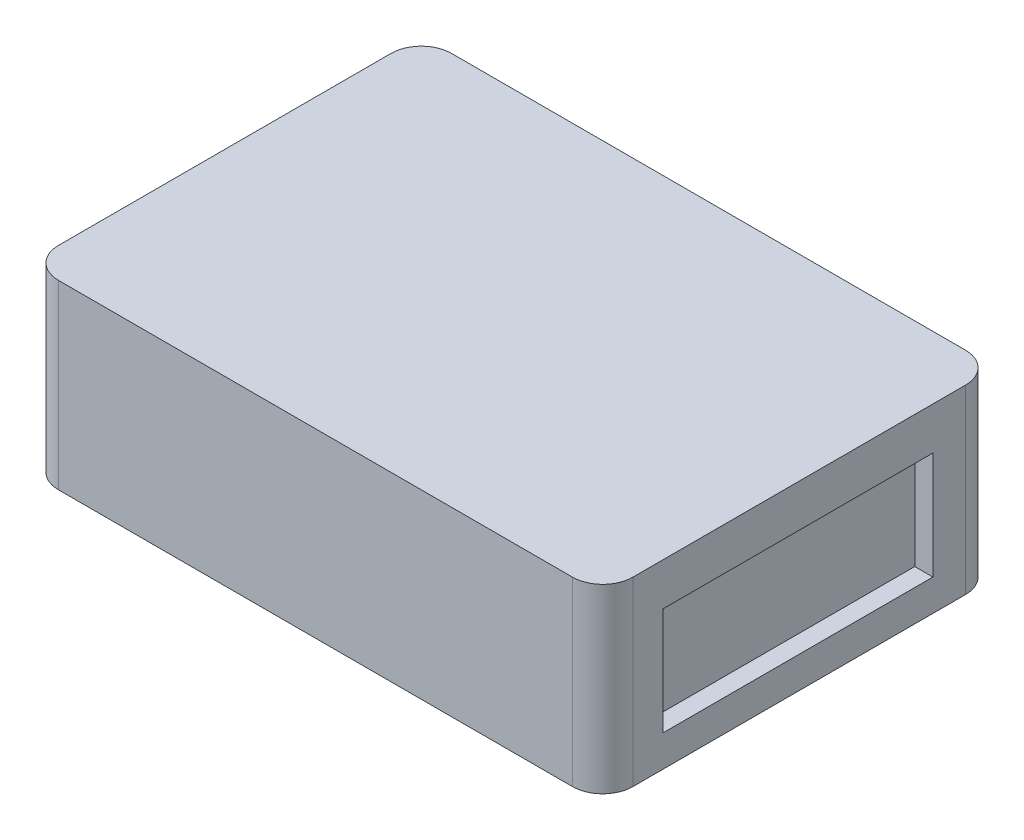
SolidWorks part; units mm, degrees
ref_plane "前视基准面" through (0, 0, 0) normal (0, 0, 1) x (1, 0, 0)
ref_plane "上视基准面" through (0, 0, 0) normal (0, 1, 0) x (1, 0, 0)
ref_plane "右视基准面" through (0, 0, 0) normal (1, 0, 0) x (0, 0, -1)
sketch "草图2" plane through (0, 0, 0) normal (0, 1, 0) x (1, 0, 0)
  line L1 (-47.5, -32.5) -> (47.5, -32.5)
  line L2 (-47.5, -32.5) -> (-47.5, 32.5)
  line L3 (-47.5, 32.5) -> (47.5, 32.5)
  line L4 (47.5, -32.5) -> (47.5, 32.5)
  line L5 (-47.5, -32.5) -> (47.5, 32.5) construction
  line L6 (-47.5, 32.5) -> (47.5, -32.5) construction
  point P0 (0, 0)
  dimension "D1" = 95
  dimension "D2" = 65
extrude "凸台-拉伸1" add sketch "草图2" along normal blind 30
fillet "圆角1" radius 5 4 edges at (-47.5, 15, -32.5) (47.5, 15, -32.5) (47.5, 15, 32.5) (-47.5, 15, 32.5)
sketch "草图3" plane through (0, 0, 0) normal (0, -1, 0) x (1, 0, 0)
  line L0 (0, 0) -> (-70.9768, 0) construction
  circle A0 centre (-40.6617, 23) radius 1.5
  circle A1 centre (-40.6617, -23) radius 1.5
  circle A2 centre (14.3383, 23) radius 1.5
  circle A3 centre (14.3383, -23) radius 1.5
  dimension "D1" = 3
  dimension "D3" = 46
  dimension "D2" = 2
  dimension "D4" = 2
extrude "切除-拉伸1" cut sketch "草图3" against normal blind 10
sketch "草图4" plane through (47.5, 0, 0) normal (1, 0, 0) x (0, 0, -1)
  line L1 (-22.5225, 22.9728) -> (22.1002, 22.9728)
  line L2 (-22.5225, 22.9728) -> (-22.5225, 5.2104)
  line L3 (-22.5225, 5.2104) -> (22.1002, 5.2104)
  line L4 (22.1002, 22.9728) -> (22.1002, 5.2104)
extrude "切除-拉伸2" cut sketch "草图4" against normal blind 3
